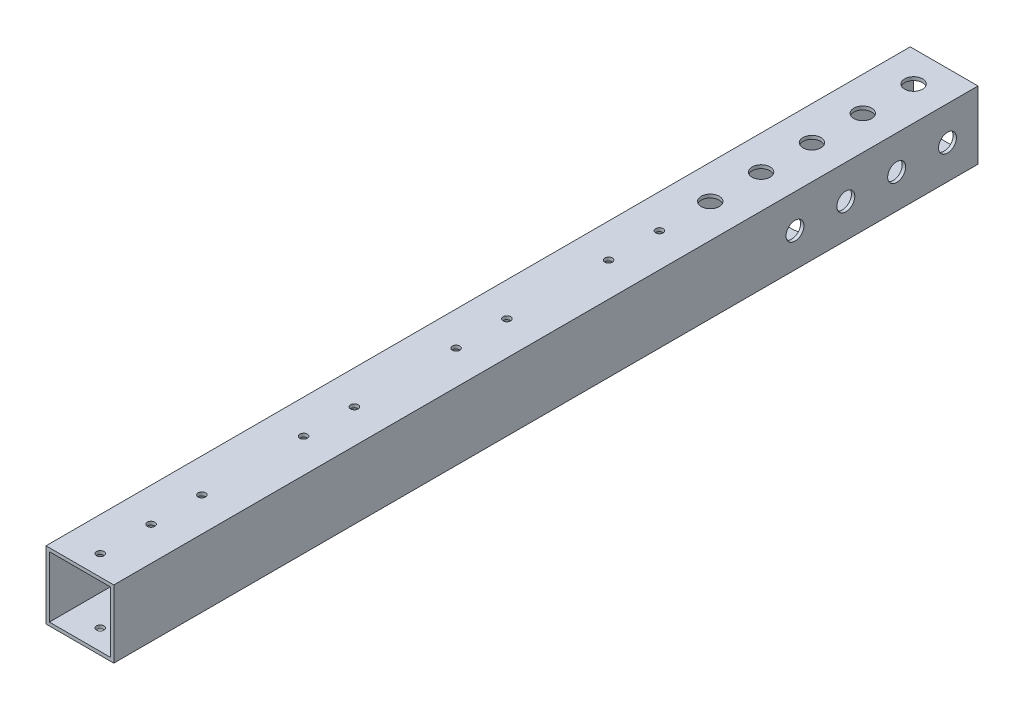
SolidWorks part; units mm, degrees
ref_plane "前视基准面" through (0, 0, 0) normal (0, 0, 1) x (1, 0, 0)
ref_plane "上视基准面" through (0, 0, 0) normal (0, 1, 0) x (1, 0, 0)
ref_plane "右视基准面" through (0, 0, 0) normal (1, 0, 0) x (0, 0, -1)
sketch "草图1" plane through (0, 0, 0) normal (0, 0, 1) x (1, 0, 0)
  line L1 (0, 0) -> (20, 0)
  line L2 (0, 0) -> (0, -20)
  line L3 (0, -20) -> (20, -20)
  line L4 (20, 0) -> (20, -20)
  line L5 (19, -19) -> (1, -19)
  line L6 (19, -19) -> (19, -1)
  line L7 (19, -1) -> (1, -1)
  line L8 (1, -19) -> (1, -1)
  dimension "D1" = 20
  dimension "D2" = 20
  dimension "D3" = 18
  dimension "D4" = 1
  dimension "D5" = 1
  dimension "D6" = 18
extrude "凸台-拉伸2" add sketch "草图1" along normal blind 255
sketch "草图2" plane through (0, -20, 0) normal (0, -1, 0) x (-1, 0, 0)
  line L0 (0, 0) -> (-20, 0) construction
  line L1 (-20, -255) -> (-20, 0) construction
  circle A0 centre (-10, -9) radius 2.65
  circle A1 centre (-10, -24) radius 2.65
  circle A2 centre (-10, -39) radius 2.65
  circle A3 centre (-10, -54) radius 2.65
  circle A4 centre (-10, -69) radius 2.65
  circle A6 centre (-10, -99) radius 1.1
  circle A8 centre (-10, -129) radius 1.1
  circle A9 centre (-10, -144) radius 1.1
  circle A11 centre (-10, -174) radius 1.1
  circle A12 centre (-10, -189) radius 1.1
  circle A14 centre (-10, -219) radius 1.1
  circle A15 centre (-10, -234) radius 1.1
  circle A16 centre (-10, -249) radius 1.1
  circle A17 centre (-10, -84) radius 2.65 [skipped]
  circle A18 centre (-10, -84) radius 1.1
  circle A19 centre (-10, -114) radius 1.1 [skipped]
  circle A20 centre (-10, -159) radius 1.1 [skipped]
  circle A21 centre (-10, -204) radius 1.1 [skipped]
  dimension "D1" = 9
  dimension "D2" = 10
  dimension "D3" = 5.3
  dimension "D5" = 2
  dimension "D8" = 2.2
  dimension "D4" = 6
  dimension "D6" = 9
  dimension "D7" = 3
extrude "切除-拉伸1" cut sketch "草图2" against normal blind 20
sketch "草图5" plane through (0, 0, 0) normal (-1, 0, 0) x (0, 0, 1)
  line L0 (255, 0) -> (0, 0) construction
  line L1 (0, 0) -> (0, -20) construction
  circle A0 centre (9, -10) radius 2.65
  circle A1 centre (24, -10) radius 2.65
  circle A2 centre (39, -10) radius 2.65
  circle A3 centre (54, -10) radius 2.65
  circle A5 centre (69, -10) radius 2.65 [skipped]
  dimension "D1" = 10
  dimension "D2" = 9
  dimension "D4" = 5.3
  dimension "D3" = 5
extrude "切除-拉伸2" cut sketch "草图5" against normal blind 20
sketch "草图6" plane through (0, -20, 0) normal (0, -1, 0) x (-1, 0, 0)
  circle A2 centre (-10, -39) radius 6
  circle A3 centre (-10, -54) radius 6
  circle A4 centre (-10, -69) radius 6
extrude "切除-拉伸3" cut sketch "草图6" against normal blind 10
